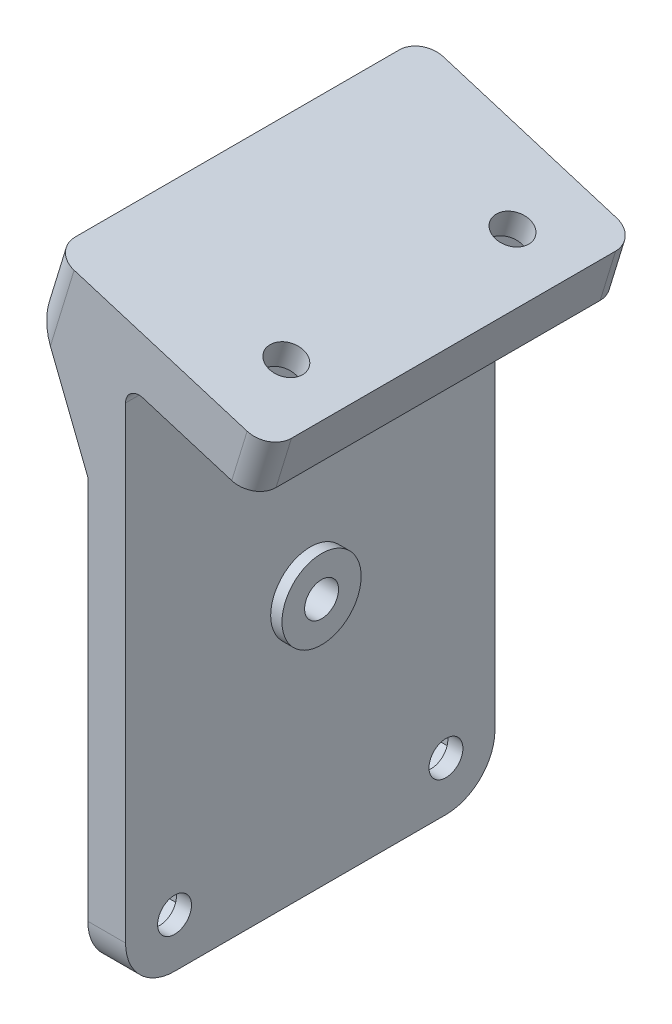
SolidWorks part; units mm, degrees
ref_plane "Plan de face" through (0, 0, 0) normal (0, 0, 1) x (1, 0, 0)
ref_plane "Plan de dessus" through (0, 0, 0) normal (0, 1, 0) x (1, 0, 0)
ref_plane "Plan de droite" through (0, 0, 0) normal (1, 0, 0) x (0, 0, -1)
sketch "Esquisse1" plane through (0, 0, 0) normal (0, 0, 1) x (1, 0, 0)
  line L0 (0, 0) -> (-28.6891, 8.7712)
  line L1 (-28.6891, 8.7712) -> (-30.7357, 2.077)
  line L2 (-30.7357, 2.077) -> (-24, 0.0177)
  line L3 (-24, 0.0177) -> (-24, -87.9823)
  line L4 (-24, -87.9823) -> (-19, -87.9823)
  line L5 (-19, -87.9823) -> (-19, -1.511)
  line L6 (-19, -1.511) -> (-2.0466, -6.6941)
  line L7 (-2.0466, -6.6941) -> (0, 0)
  line L8 (-28.6891, 8.7712) -> (-4.288, 8.7712) construction
  dimension "D1" = 7
  dimension "D2" = 30
  dimension "D3" = 17
  dimension "D4" = 19
  dimension "D5" = 5
  dimension "D6" = 88
extrude "Boss.-Extru.1" add sketch "Esquisse1" along normal blind 49
sketch "Esquisse2" plane through (0, 0, 0) normal (0.2924, 0.9563, 0) x (0.9563, -0.2924, 0)
  line L0 (-7.5, 0) -> (-7.5, -49) construction
  line L1 (0, 0) -> (-30, 0) construction
  line L2 (0, -49) -> (-30, -49) construction
  line L3 (0, -49) -> (0, 0) construction
  line L4 (-7.5, -24.5) -> (-17.5689, -24.5) construction
  circle A0 centre (-7.5, -9.5) radius 2.25
  circle A1 centre (-7.5, -39.5) radius 2.25
  dimension "D2" = 4.5
  dimension "D3" = 30
  dimension "D1" = 7.5
extrude "Enlèv. mat.-Extru.1" cut sketch "Esquisse2" against normal up to next and the other way through all
sketch "Esquisse3" plane through (-19, 0, 0) normal (1, 0, 0) x (0, 0, -1)
  line L0 (0, -65.9823) -> (-49, -65.9823) construction
  line L1 (0, -87.9823) -> (0, -1.511) construction
  line L2 (-49, -87.9823) -> (-49, -1.511) construction
  line L3 (-49, -87.9823) -> (0, -87.9823) construction
  line L4 (-24.5, -65.9823) -> (-24.5, -37.9823) construction
  circle A0 centre (-42.5, -65.9823) radius 2.25
  circle A1 centre (-6.5, -65.9823) radius 2.25
  circle A2 centre (-24.5, -37.9823) radius 2.25
  dimension "D2" = 4.5
  dimension "D3" = 36
  dimension "D4" = 28
  dimension "D1" = 22
extrude "Enlèv. mat.-Extru.2" cut sketch "Esquisse3" against normal up to next
sketch "Esquisse4" plane through (-19, 0, 0) normal (1, 0, 0) x (0, 0, -1)
  line L0 (-42.5, -65.9823) -> (-49, -65.9823) construction
  line L3 (-24.5, -87.9823) -> (-42.5, -72.4823)
  line L5 (-49, -87.9823) -> (0, -87.9823) construction
  line L6 (-42.5, -72.4823) -> (-42.5, -65.9823) construction
  line L7 (-24.5, -87.9823) -> (-24.5, -37.1138) construction
  line L8 (-6.5, -72.4823) -> (-6.5, -65.9823) construction
  line L9 (-6.5, -65.9823) -> (0, -65.9823) construction
  line L10 (-24.5, -87.9823) -> (-6.5, -72.4823)
  line L11 (-49, -65.9823) -> (-50, -65.9823)
  line L12 (-50, -65.9823) -> (-50, -88.9823)
  line L13 (-50, -88.9823) -> (1, -88.9823)
  line L14 (1, -88.9823) -> (1, -65.9823)
  line L15 (1, -65.9823) -> (0, -65.9823)
  arc A0 (-49, -65.9823) -> (-42.5, -72.4823) centre (-42.5, -65.9823) ccw
  arc A1 (0, -65.9823) -> (-6.5, -72.4823) centre (-6.5, -65.9823) cw
  dimension "D1" = 6.5
  dimension "D2" = 1
  dimension "D3" = 1
extrude "Enlèv. mat.-Extru.3" cut sketch "Esquisse4" against normal up to next
fillet "Congé1" radius 3 1 edges at (-21.5, -87.9823, 24.5)
sketch "Esquisse5" plane through (0, 0, 0) normal (0.2924, 0.9563, 0) x (0.9563, -0.2924, 0)
  line L0 (0, -24.5) -> (-19.2375, -24.5) construction
  line L1 (-3.95, -11.5496) -> (-3.95, -7.4504)
  line L2 (-3.95, -7.4504) -> (-7.5, -5.4008)
  line L3 (-7.5, -5.4008) -> (-11.05, -7.4504)
  line L4 (-11.05, -7.4504) -> (-11.05, -11.5496)
  line L5 (-11.05, -11.5496) -> (-7.5, -13.5992)
  line L6 (-7.5, -13.5992) -> (-3.95, -11.5496)
  line L7 (0, -49) -> (0, 0) construction
  line L8 (-7.5, -35.4008) -> (-3.95, -37.4504)
  line L9 (-11.05, -37.4504) -> (-7.5, -35.4008)
  line L10 (-11.05, -41.5496) -> (-11.05, -37.4504)
  line L11 (-7.5, -43.5992) -> (-11.05, -41.5496)
  line L12 (-3.95, -41.5496) -> (-7.5, -43.5992)
  line L13 (-3.95, -37.4504) -> (-3.95, -41.5496)
  circle A0 centre (-7.5, -9.5) radius 3.55 construction
  circle A1 centre (-7.5, -39.5) radius 3.55 construction
  dimension "D1" = 7.1
extrude "Enlèv. mat.-Extru.4" cut sketch "Esquisse5" along normal blind 3.5 from vertex
sketch "Esquisse6" plane through (0, 0, 49) normal (0, 0, 1) x (1, 0, 0)
  line L0 (-30.7357, 2.077) -> (-24, -14.9823)
  line L1 (-24, 0.0177) -> (-24, -65.9823) construction
  line L2 (-24, -14.9823) -> (-24, 0.0177)
  line L3 (-24, 0.0177) -> (-30.7357, 2.077)
  dimension "D1" = 15
extrude "Boss.-Extru.2" add sketch "Esquisse6" against normal up to vertex (49 mm away)
fillet "Congé2" radius 1.8 1 edges at (-19, -1.511, 24.5)
fillet "Congé3" radius 3 4 edges at (-29.7124, 5.4241, 0) (-1.0233, -3.3471, 0) (-1.0233, -3.3471, 49) (-29.7124, 5.4241, 49)
sketch "Esquisse8" plane through (-19, 0, 0) normal (1, 0, 0) x (0, 0, -1)
  line L0 (-42.5, -72.4823) -> (-6.5, -72.4823)
  line L1 (-6.5, -72.4823) -> (-6.5, -88.4823)
  line L2 (-6.5, -88.4823) -> (-42.5, -88.4823)
  line L3 (-42.5, -88.4823) -> (-42.5, -72.4823)
  dimension "D1" = 16
extrude "Enlèv. mat.-Extru.5" cut sketch "Esquisse8" against normal through all both and the other way through all
sketch "Esquisse9" plane through (-19, 0, 0) normal (1, 0, 0) x (0, 0, -1)
  circle A0 centre (-24.5, -37.9823) radius 5.25
  circle A1 centre (-24.5, -37.9823) radius 2.25
  circle A3 centre (-24.5, -37.9823) radius 2.25 construction
  dimension "D1" = 3
extrude "Boss.-Extru.3" add sketch "Esquisse9" along normal blind 1.5
sketch "Esquisse10" plane through (-24, 0, 0) normal (-1, 0, 0) x (0, 0, 1)
  line L1 (28.05, -40.0319) -> (28.05, -35.9327)
  line L2 (28.05, -35.9327) -> (24.5, -33.8831)
  line L3 (24.5, -33.8831) -> (20.95, -35.9327)
  line L4 (20.95, -35.9327) -> (20.95, -40.0319)
  line L5 (20.95, -40.0319) -> (24.5, -42.0815)
  line L6 (24.5, -42.0815) -> (28.05, -40.0319)
  line L7 (10.05, -68.0319) -> (10.05, -63.9327)
  line L8 (10.05, -63.9327) -> (6.5, -61.8831)
  line L9 (6.5, -61.8831) -> (2.95, -63.9327)
  line L10 (2.95, -63.9327) -> (2.95, -68.0319)
  line L11 (2.95, -68.0319) -> (6.5, -70.0815)
  line L12 (6.5, -70.0815) -> (10.05, -68.0319)
  line L13 (46.05, -68.0319) -> (46.05, -63.9327)
  line L14 (46.05, -63.9327) -> (42.5, -61.8831)
  line L15 (42.5, -61.8831) -> (38.95, -63.9327)
  line L16 (38.95, -63.9327) -> (38.95, -68.0319)
  line L17 (38.95, -68.0319) -> (42.5, -70.0815)
  line L18 (42.5, -70.0815) -> (46.05, -68.0319)
  circle A0 centre (24.5, -37.9823) radius 3.55 construction
  circle A1 centre (6.5, -65.9823) radius 3.55 construction
  circle A2 centre (42.5, -65.9823) radius 3.55 construction
  dimension "D1" = 7.1
extrude "Enlèv. mat.-Extru.6" cut sketch "Esquisse10" against normal blind 3
fillet "Congé4" [suppressed] radius 3
